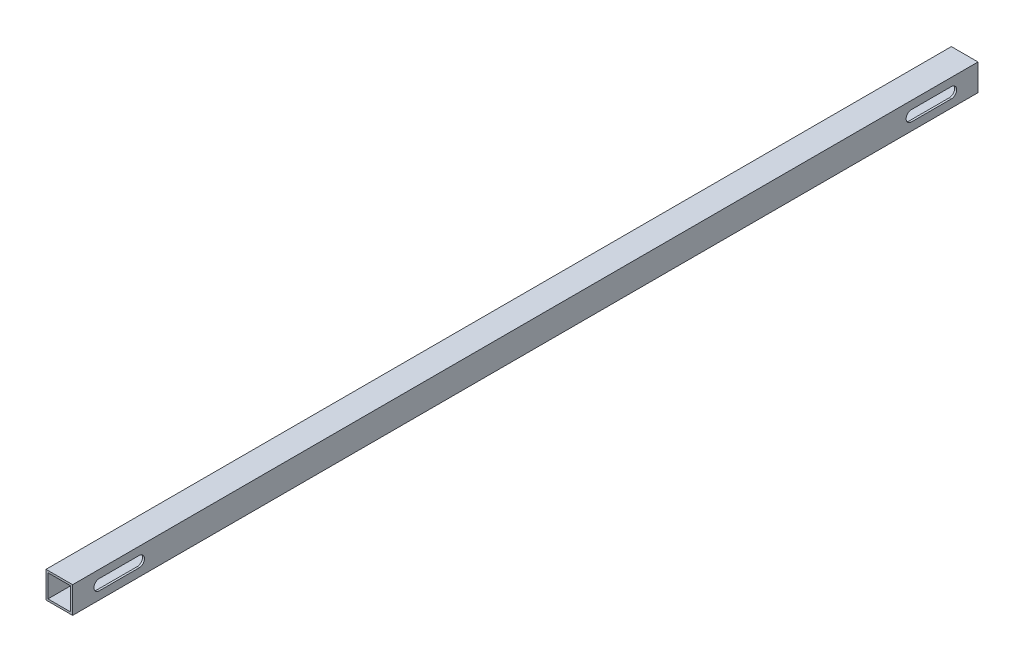
SolidWorks part; units mm, degrees
ref_plane "正面" through (0, 0, 0) normal (0, 0, 1) x (1, 0, 0)
ref_plane "平面" through (0, 0, 0) normal (0, 1, 0) x (1, 0, 0)
ref_plane "右側面" through (0, 0, 0) normal (1, 0, 0) x (0, 0, -1)
sketch "ｽｹｯﾁ1" plane through (0, 0, 0) normal (0, 0, 1) x (1, 0, 0)
  line L0 (-8.5, 8.5) -> (8.5, 8.5)
  line L1 (-10, 10) -> (10, 10)
  line L2 (-10, 10) -> (-10, -10)
  line L3 (-10, -10) -> (10, -10)
  line L4 (10, 10) -> (10, -10)
  line L5 (8.5, 8.5) -> (8.5, -8.5)
  line L6 (-8.5, -8.5) -> (8.5, -8.5)
  line L7 (-8.5, 8.5) -> (-8.5, -8.5)
  point P0 (0, 0)
  dimension "D1" = 20
  dimension "D2" = 20
  dimension "D3" = 1.5
extrude "ﾎﾞｽ - 押し出し1" add sketch "ｽｹｯﾁ1" along normal blind 680
sketch "ｽｹｯﾁ2" plane through (-10, 0, 0) normal (-1, 0, 0) x (0, 0, 1)
  line L0 (660, 0) -> (630, 0) construction
  line L1 (660, -4) -> (630, -4)
  line L2 (660, 4) -> (630, 4)
  line L3 (680, 10) -> (680, -10) construction
  line L4 (340, 10) -> (340, -68.0313) construction
  line L5 (680, 10) -> (0, 10) construction
  line L6 (20, 0) -> (50, 0) construction
  line L7 (20, -4) -> (50, -4)
  line L8 (20, 4) -> (50, 4)
  arc A0 (660, -4) -> (660, 4) centre (660, 0) ccw
  arc A1 (630, 4) -> (630, -4) centre (630, 0) ccw
  arc A2 (20, -4) -> (20, 4) centre (20, 0) cw
  arc A3 (50, 4) -> (50, -4) centre (50, 0) cw
  point P3 (645, 0)
  point P16 (35, 0)
  dimension "D3" = 20
  dimension "D1" = 8
  dimension "D2" = 30
extrude "ｶｯﾄ - 押し出し1" cut sketch "ｽｹｯﾁ2" against normal through all
